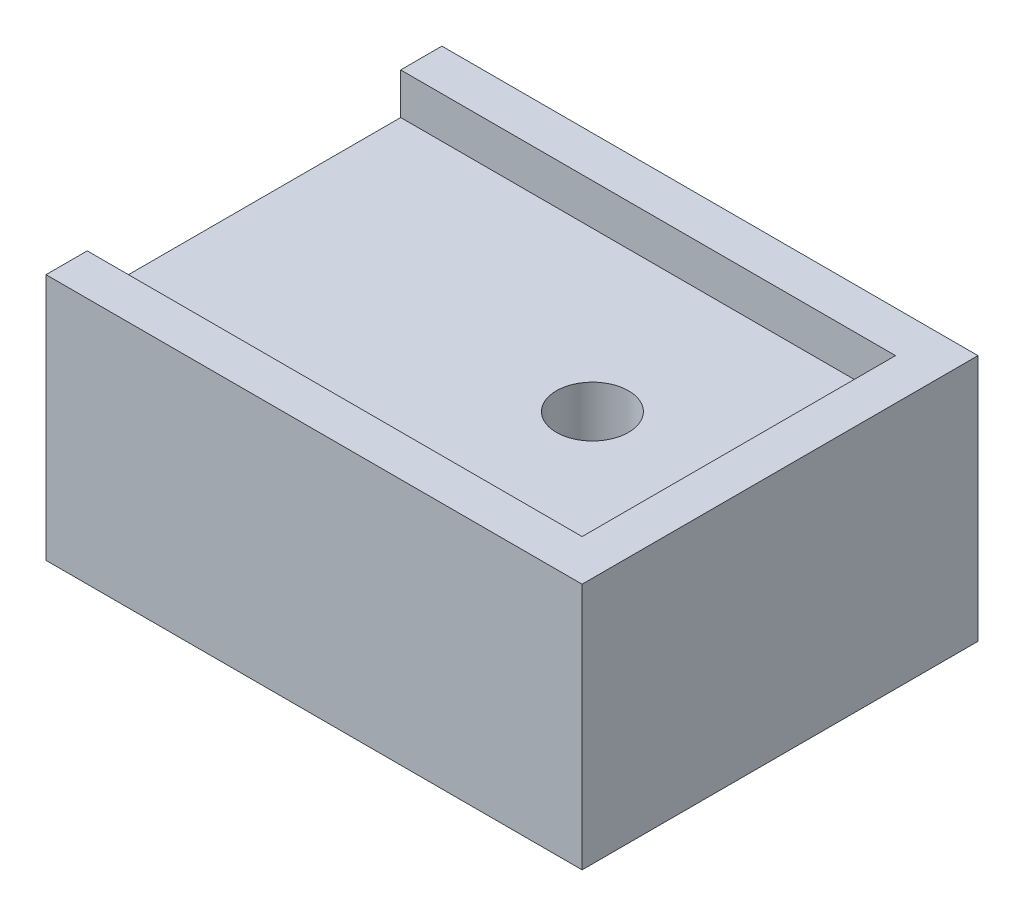
SolidWorks part; units mm, degrees
ref_plane "Front" through (0, 0, 0) normal (0, 0, 1) x (1, 0, 0)
ref_plane "Top" through (0, 0, 0) normal (0, 1, 0) x (1, 0, 0)
ref_plane "Right" through (0, 0, 0) normal (1, 0, 0) x (0, 0, -1)
sketch "Sketch1" plane through (0, 0, 0) normal (0, 1, 0) x (1, 0, 0)
  line L1 (-12, -7.6) -> (12, -7.6)
  line L2 (-12, -7.6) -> (-12, 7.6)
  line L3 (-12, 7.6) -> (12, 7.6)
  line L4 (12, -7.6) -> (12, 7.6)
  line L5 (-12, -7.6) -> (12, 7.6) construction
  line L6 (-12, 7.6) -> (12, -7.6) construction
  point P0 (0, 0)
  dimension "D1" = 24
  dimension "D2" = 15.2
extrude "Boss-Extrude1" add sketch "Sketch1" along normal blind 10
sketch "Sketch3" plane through (0, 10, 0) normal (0, 1, 0) x (1, 0, 0)
  circle A0 centre (5, -0.1) radius 1.75
  dimension "D1" = 3.5
extrude "Cut-Extrude1" cut sketch "Sketch3" against normal blind 10
sketch "Sketch4" plane through (0, 0, 0) normal (0, -1, 0) x (-1, 0, 0)
  line L6 (12, -9.6) -> (12, -7.6)
  line L7 (12, -7.6) -> (-12, -7.6)
  line L8 (-12, -7.6) -> (-12, 7.6)
  line L9 (-14, 9.6) -> (12, 9.6)
  line L10 (12, -9.6) -> (-14, -9.6)
  line L11 (-14, -9.6) -> (-14, 9.6)
  line L12 (-14, 9.6) -> (12, 9.6)
  line L13 (12, -9.6) -> (-14, -9.6)
  line L14 (-14, -9.6) -> (-14, 9.6)
  line L15 (-12, 7.6) -> (12, 7.6)
  line L16 (12, 7.6) -> (12, 9.6)
  dimension "D1" = 2
extrude "Boss-Extrude2" add sketch "Sketch4" against normal blind 12
